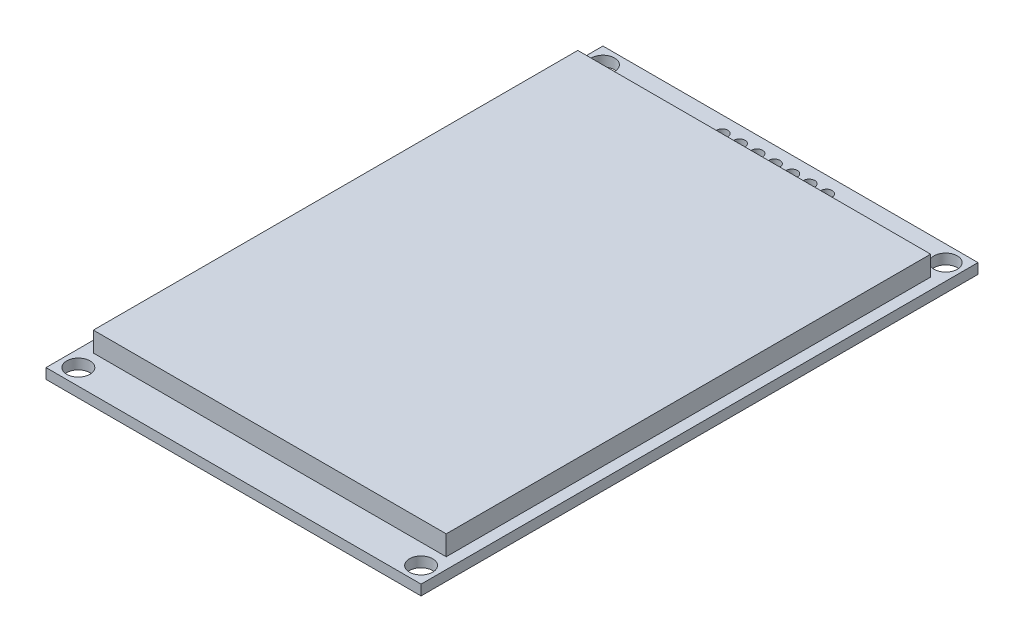
SolidWorks part; units mm, degrees
ref_plane "Front Plane" through (0, 0, 0) normal (0, 0, 1) x (1, 0, 0)
ref_plane "Top Plane" through (0, 0, 0) normal (0, 1, 0) x (1, 0, 0)
ref_plane "Right Plane" through (0, 0, 0) normal (1, 0, 0) x (0, 0, -1)
sketch "Sketch1" plane through (0, 0, 0) normal (0, 1, 0) x (1, 0, 0)
  line L0 (-27.37, 0) -> (27.37, 0) construction
  line L1 (-27.37, -40.64) -> (27.37, -40.64)
  line L2 (-27.37, -40.64) -> (-27.37, 40.64)
  line L3 (-27.37, 40.64) -> (27.37, 40.64)
  line L4 (27.37, -40.64) -> (27.37, 40.64)
  line L5 (-27.37, -40.64) -> (27.37, 40.64) construction
  line L6 (-27.37, 40.64) -> (27.37, -40.64) construction
  line L7 (0, -40.64) -> (0, 40.64) construction
  line L8 (0, 40.64) -> (0, 0) construction
  line L9 (-25.01, 38.28) -> (25.01, 38.28) construction
  line L10 (0, 38.28) -> (2.54, 38.28) construction
  line L11 (0, 38.28) -> (-2.54, 38.28) construction
  circle A0 centre (-25.01, 38.28) radius 1.7
  circle A1 centre (-25.01, 38.28) radius 2.36 construction
  circle A2 centre (25.01, 38.28) radius 2.36 construction
  circle A3 centre (25.01, 38.28) radius 1.7
  circle A4 centre (-25.01, -38.28) radius 2.36 construction
  circle A5 centre (-25.01, -38.28) radius 1.7
  circle A6 centre (25.01, -38.28) radius 1.7
  circle A7 centre (25.01, -38.28) radius 2.36 construction
  circle A8 centre (0, 38.28) radius 0.83
  circle A9 centre (2.54, 38.28) radius 0.83
  circle A10 centre (5.08, 38.28) radius 0.83
  circle A11 centre (7.62, 38.28) radius 0.83
  circle A12 centre (-2.54, 38.28) radius 0.83
  circle A13 centre (-5.08, 38.28) radius 0.83
  circle A14 centre (-7.62, 38.28) radius 0.83
  point P0 (0, 0)
  dimension "D3" = 76.56
  dimension "D4" = 3.4
  dimension "D5" = 1.66
  dimension "D1" = 81.28
  dimension "D2" = 54.74
  dimension "D6" = 4
  dimension "D7" = 2.54
  dimension "D9" = 2.54
  dimension "D8" = 4
extrude "Boss-Extrude1" add sketch "Sketch1" along normal blind 1.5
sketch "Sketch2" plane through (0, 1.5, 0) normal (0, 1, 0) x (1, 0, 0)
  line L1 (-25.75, -35.35) -> (25.75, -35.35)
  line L2 (-25.75, -35.35) -> (-25.75, 35.35)
  line L3 (-25.75, 35.35) -> (25.75, 35.35)
  line L4 (25.75, -35.35) -> (25.75, 35.35)
  line L5 (-25.75, -35.35) -> (25.75, 35.35) construction
  line L6 (-25.75, 35.35) -> (25.75, -35.35) construction
  point P0 (0, 0)
  dimension "D1" = 70.7
  dimension "D2" = 51.5
extrude "Boss-Extrude2" add sketch "Sketch2" along normal blind 2.9
sketch "Sketch3" plane through (0, 0, 0) normal (0, -1, 0) x (1, 0, 0)
  line L0 (-6.35, -37.01) -> (6.35, -37.01)
  line L1 (-8.89, -39.55) -> (-6.35, -39.55)
  line L2 (-8.89, -39.55) -> (-8.89, -37.01)
  line L3 (-8.89, -37.01) -> (-6.35, -37.01)
  line L4 (-6.35, -39.55) -> (-6.35, -37.01) construction
  line L5 (-8.89, -39.55) -> (-6.35, -37.01) construction
  line L6 (-8.89, -37.01) -> (-6.35, -39.55) construction
  line L7 (6.35, -39.55) -> (8.89, -39.55)
  line L8 (6.35, -39.55) -> (6.35, -37.01) construction
  line L9 (6.35, -37.01) -> (8.89, -37.01)
  line L10 (8.89, -39.55) -> (8.89, -37.01)
  line L11 (6.35, -39.55) -> (8.89, -37.01) construction
  line L12 (6.35, -37.01) -> (8.89, -39.55) construction
  line L13 (6.35, -39.55) -> (-6.35, -39.55)
  point P0 (-7.62, -38.28)
  point P6 (7.62, -38.28)
  dimension "D1" = 2.54
  dimension "D2" = 2.54
  dimension "D3" = 2.54
  dimension "D4" = 2.54
extrude "Boss-Extrude3" add sketch "Sketch3" along normal blind 2.54
